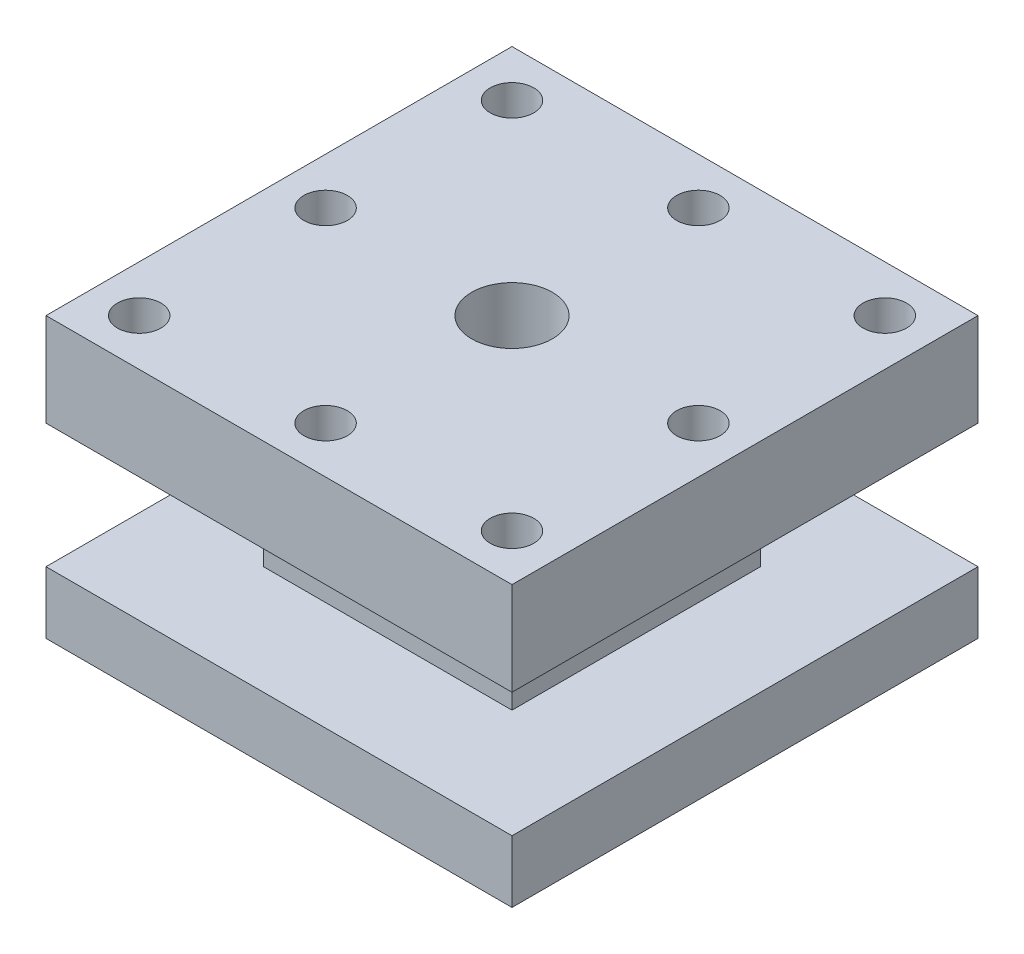
SolidWorks part; units mm, degrees
material "AISI 1015 Steel, Cold Drawn (SS)"
ref_plane "Front Plane" through (0, 0, 0) normal (0, 0, 1) x (1, 0, 0)
ref_plane "Top Plane" through (0, 0, 0) normal (0, 1, 0) x (1, 0, 0)
ref_plane "Right Plane" through (0, 0, 0) normal (1, 0, 0) x (0, 0, -1)
sketch "Sketch2" plane through (0, 0, 0) normal (0, 1, 0) x (1, 0, 0)
  line L1 (-75, 75) -> (75, 75)
  line L2 (-75, 75) -> (-75, -75)
  line L3 (-75, -75) -> (75, -75)
  line L4 (75, 75) -> (75, -75)
  line L5 (-75, 75) -> (75, -75) construction
  line L6 (-75, -75) -> (75, 75) construction
  point P0 (0, 0)
  dimension "D1" = 150
  dimension "D2" = 150
extrude "Boss-Extrude1" add sketch "Sketch2" against normal blind 30
sketch "Sketch3" plane through (0, -30, 0) normal (0, -1, 0) x (1, 0, 0)
  line L1 (-40, 40) -> (40, 40)
  line L2 (-40, 40) -> (-40, -40)
  line L3 (-40, -40) -> (40, -40)
  line L4 (40, 40) -> (40, -40)
  line L5 (-40, 40) -> (40, -40) construction
  line L6 (-40, -40) -> (40, 40) construction
  point P0 (0, 0)
  dimension "D1" = 80
  dimension "D2" = 80
extrude "Boss-Extrude2" add sketch "Sketch3" along normal blind 40
sketch "Sketch4" plane through (0, -70, 0) normal (0, -1, 0) x (1, 0, 0)
  line L4 (-75, -75) -> (75, -75)
  line L5 (75, -75) -> (75, 75)
  line L6 (75, 75) -> (-75, 75)
  line L7 (-75, 75) -> (-75, -75)
  line L8 (-75, -75) -> (75, -75)
  line L9 (75, -75) -> (75, 75)
  line L10 (75, 75) -> (-75, 75)
  line L11 (-75, 75) -> (-75, -75)
  dimension "D1" = 0
extrude "Boss-Extrude3" add sketch "Sketch4" along normal blind 20
hole_wizard "Hole1" positions "Sketch5" profile "Sketch6" legacy
sketch "Sketch5" plane through (0, -90, 0) normal (0, -1, 0) x (-1, 0, 0)
  point P0 (0, 0)
sketch "Sketch6" plane through (0, -90, 0) normal (1, 0, 0) x (0, 0, -1)
  line L0 (0, 0) -> (0, 100)
  line L1 (0, 100) -> (13, 100)
  line L2 (13, 100) -> (13, 10)
  line L3 (13, 10) -> (30, 10)
  line L4 (30, 10) -> (30, 0)
  line L5 (30, 0) -> (0, 0)
  line L6 (0, 110) -> (0, -10) construction
  dimension "Diameter" = 26
  dimension "Depth" = 100
  dimension "C-Bore Diameter" = 60
  dimension "C-Bore Depth" = 10
hole_wizard "M16 Tapped Hole2" positions "Sketch7" profile "Sketch8" tap size "M16" standard "ISO"
sketch "Sketch7" plane through (0, 0, 0) normal (0, 1, 0) x (1, 0, 0)
  line L1 (-60, 60) -> (60, 60) construction
  line L2 (-60, 60) -> (-60, -60) construction
  line L3 (-60, -60) -> (60, -60) construction
  line L4 (60, 60) -> (60, -60) construction
  line L5 (-60, 60) -> (60, -60) construction
  line L6 (-60, -60) -> (60, 60) construction
  point P2 (60, -60)
  point P5 (-60, 60)
  point P6 (-60, -60)
  point P7 (60, 60)
  point P76 (0, 60)
  point P80 (-60, 0)
  point P84 (0, -60)
  point P88 (60, 0)
  dimension "D1" = 120
  dimension "D2" = 120
  dimension "D3" = 60
  dimension "D4" = 60
sketch "Sketch8" plane through (60, 0, 60) normal (1, 0, 0) x (0, 0, 1)
  line L0 (0, 0) -> (0, 30)
  line L1 (0, 30) -> (7, 30)
  line L2 (7, 30) -> (7, 0)
  line L5 (7, 0) -> (0, 0)
  line L11 (0, -6.35) -> (0, 107.95) construction
  dimension "Thru Tap Drill Dia." = 14
  dimension "Thru Tap Drill Depth" = 30
cosmetic thread "Hole Thread1" parameters "D2"=16
cosmetic thread "Hole Thread2" parameters "D2"=16
cosmetic thread "Hole Thread3" parameters "D2"=16
cosmetic thread "Hole Thread4" parameters "D2"=16
cosmetic thread "Hole Thread5" parameters "D2"=16
cosmetic thread "Hole Thread6" parameters "D2"=16
cosmetic thread "Hole Thread7" parameters "D2"=16
cosmetic thread "Hole Thread8" parameters "D2"=16
hole_wizard "Ø10.0 (10) Diameter Hole1" positions "Sketch9" profile "Sketch10" hole size "Ø10.0" standard "ANSI Metric"
sketch "Sketch9" plane through (0, -90, 0) normal (0, -1, 0) x (-1, 0, 0)
  line L1 (-52, 52) -> (52, 52)
  line L2 (-52, 52) -> (-52, -52)
  line L3 (-52, -52) -> (52, -52)
  line L4 (52, 52) -> (52, -52)
  line L5 (-52, 52) -> (52, -52) construction
  line L6 (-52, -52) -> (52, 52) construction
  point P90 (0, -52)
  point P92 (52, 0)
  point P94 (0, 52)
  point P96 (-52, 0)
  dimension "D1" = 104
  dimension "D2" = 104
  dimension "D3" = 52
  dimension "D4" = 52
sketch "Sketch10" plane through (52, -90, 0) normal (1, 0, 0) x (0, 0, -1)
  line L0 (0, 0) -> (0, 19.0043)
  line L1 (0, 19.0043) -> (5, 16)
  line L2 (5, 16) -> (5, 0)
  line L5 (5, 0) -> (0, 0)
  line L10 (0, 19.0043) -> (-5, 16) construction
  line L11 (0, -6.35) -> (0, 107.95) construction
  dimension "Hole Dia." = 10
  dimension "Hole Depth" = 16
  dimension "Drill Angle" = 118
chamfer "Chamfer1" distance 2 angle 45 1 edges at (0, -90, -30)
